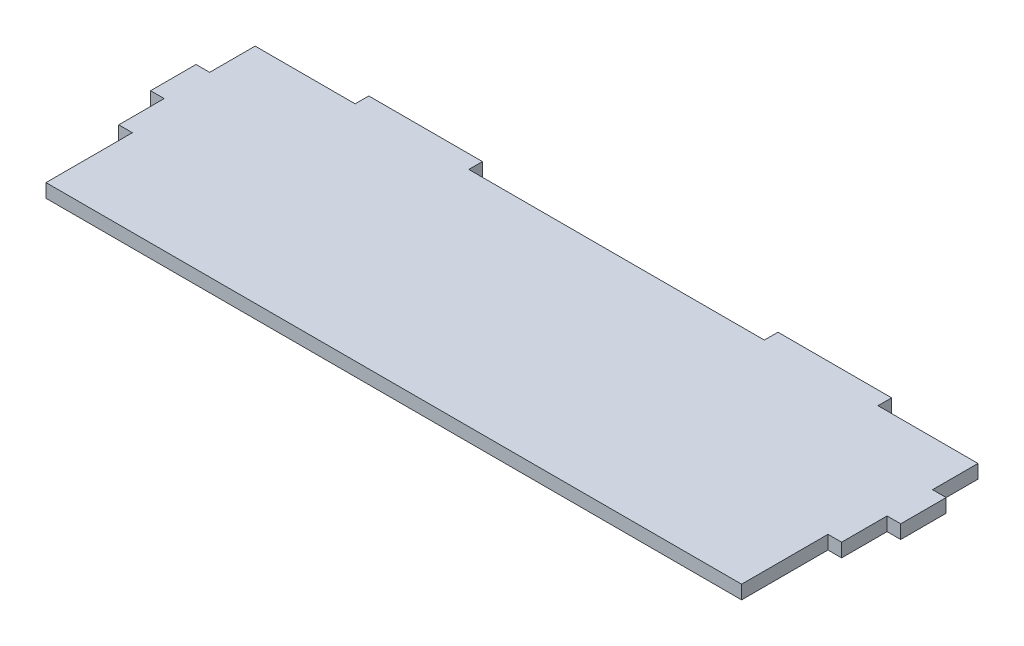
SolidWorks part; units mm, degrees
ref_plane "Front Plane" through (0, 0, 0) normal (0, 0, 1) x (1, 0, 0)
ref_plane "Top Plane" through (0, 0, 0) normal (0, 1, 0) x (1, 0, 0)
ref_plane "Right Plane" through (0, 0, 0) normal (1, 0, 0) x (0, 0, -1)
sketch "Sketch2" plane through (0, 0, 0) normal (0, 1, 0) x (1, 0, 0)
  line L0 (-79.5, 14.9712) -> (-79.5, 24.9712)
  line L1 (76.5, -24.0288) -> (-76.5, -24.0288)
  line L2 (79.5, -5.0288) -> (79.5, 4.9712)
  line L3 (79.5, 24.9712) -> (57.5, 24.9712)
  line L4 (-79.5, -5.0288) -> (-79.5, 4.9712)
  line L5 (76.5, -24.0288) -> (-79.5, 24.9712) construction
  line L6 (79.5, 24.9712) -> (-76.5, -24.0288) construction
  line L7 (-79.5, 14.9712) -> (-82.5, 14.9712)
  line L8 (-57.5, 24.9712) -> (-79.5, 24.9712)
  line L9 (-79.5, 4.9712) -> (-82.5, 4.9712)
  line L10 (-82.5, 14.9712) -> (-82.5, 4.9712)
  line L11 (-79.5, -5.0288) -> (-76.5, -5.0288)
  line L12 (79.5, 14.9712) -> (79.5, 24.9712)
  line L13 (32.5, 24.9712) -> (-32.5, 24.9712)
  line L14 (-76.5, -5.0288) -> (-76.5, -24.0288)
  line L15 (79.5, 14.9712) -> (82.5, 14.9712)
  line L17 (79.5, 4.9712) -> (82.5, 4.9712)
  line L18 (82.5, 14.9712) -> (82.5, 4.9712)
  line L19 (79.5, -5.0288) -> (76.5, -5.0288)
  line L22 (76.5, -5.0288) -> (76.5, -24.0288)
  line L24 (-57.5, 24.9712) -> (-57.5, 27.9712)
  line L25 (-57.5, 27.9712) -> (-32.5, 27.9712)
  line L26 (-32.5, 24.9712) -> (-32.5, 27.9712)
  line L28 (32.5, 24.9712) -> (32.5, 27.9712)
  line L29 (32.5, 27.9712) -> (57.5, 27.9712)
  line L30 (57.5, 24.9712) -> (57.5, 27.9712)
  point P0 (0, 0)
  dimension "D1" = 159
  dimension "D2" = 3
  dimension "D3" = 49
  dimension "D6" = 10
  dimension "D7" = 10
  dimension "D9" = 25
  dimension "D10" = 25
  dimension "D11" = 65
  dimension "D12" = 22
  dimension "D13" = 3
  dimension "D14" = 3
  dimension "D15" = 3
  dimension "D16" = 3
  dimension "D17" = 10
extrude "Boss-Extrude1" add sketch "Sketch2" along normal blind 3
